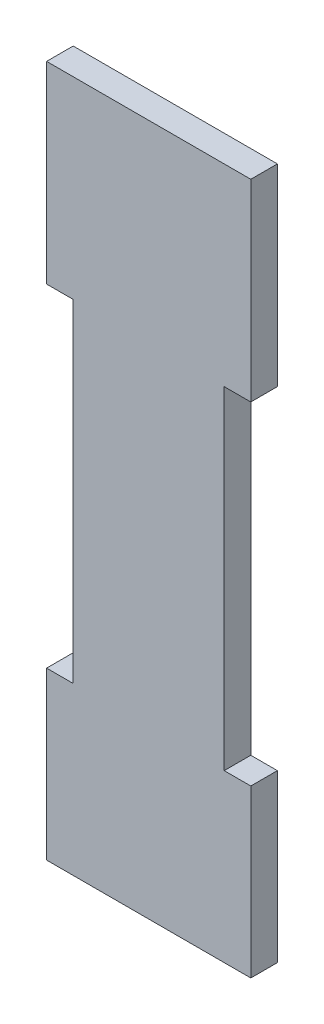
SolidWorks part; units mm, degrees
ref_plane "Спереди" through (0, 0, 0) normal (0, 0, 1) x (1, 0, 0)
ref_plane "Сверху" through (0, 0, 0) normal (0, 1, 0) x (1, 0, 0)
ref_plane "Справа" through (0, 0, 0) normal (1, 0, 0) x (0, 0, -1)
sketch "Эскиз1" plane through (0, 0, 0) normal (0, 0, 1) x (1, 0, 0)
  line L1 (0, 0) -> (-10, 0)
  line L2 (13.7, 25) -> (13.7, 75)
  line L4 (-9, 25) -> (-9, 75)
  line L6 (-13, 100) -> (-13, 104)
  line L7 (13.7, 75) -> (17.7, 75)
  line L8 (17.7, 100) -> (17.7, 75)
  line L10 (-13, 104) -> (17.7, 104)
  line L11 (-9, 75) -> (-13, 75)
  line L12 (-13, 100) -> (-13, 75)
  line L13 (0, 0) -> (17.7, 0)
  line L14 (17.7, 100) -> (17.7, 104)
  line L15 (13.7, 25) -> (17.7, 25)
  line L16 (17.7, 0) -> (17.7, 25)
  line L17 (-10, 0) -> (-13, 0)
  line L19 (-9, 25) -> (-13, 25)
  line L20 (-13, 0) -> (-13, 25)
  dimension "D1" = 100
  dimension "D2" = 22.7
  dimension "D3" = 25
  dimension "D4" = 4
  dimension "D5" = 4
extrude "Бобышка-Вытянуть1" add sketch "Эскиз1" along normal blind 4
